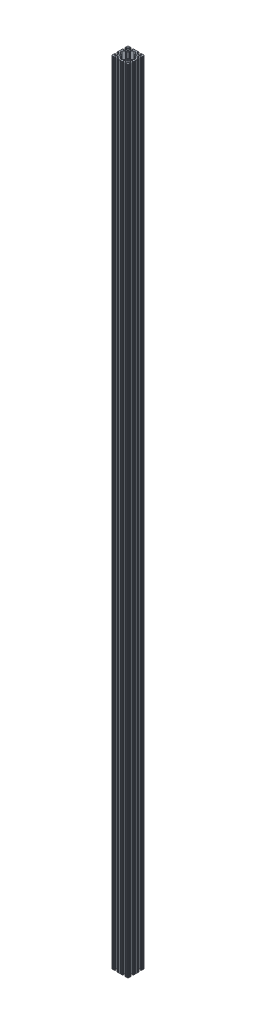
SolidWorks part; units mm, degrees
ref_plane "Piano frontale" through (0, 0, 0) normal (0, 0, 1) x (1, 0, 0)
ref_plane "Piano superiore" through (0, 0, 0) normal (0, 1, 0) x (1, 0, 0)
ref_plane "Piano destro" through (0, 0, 0) normal (1, 0, 0) x (0, 0, -1)
ref_plane "Piano1" through (0, 0, 0) normal (0, -1, 0) x (1, 0, 0)
sketch "Schizzo1" plane through (0, 0, 0) normal (0, -1, 0) x (1, 0, 0)
  line L0 (16.5037, -39.4963) -> (13.5247, -39.4963)
  line L1 (12.1105, -38.9105) -> (6.0284, -32.8284)
  line L2 (6.0284, -27.1716) -> (12.1105, -21.0895)
  line L3 (13.5247, -20.5037) -> (16.5037, -20.5037)
  line L4 (20.5037, -16.5037) -> (20.5037, -13.5247)
  line L5 (21.0895, -12.1105) -> (27.1716, -6.0284)
  line L6 (32.8284, -6.0284) -> (38.9105, -12.1105)
  line L7 (39.4963, -13.5247) -> (39.4963, -16.5037)
  line L8 (43.4963, -20.5037) -> (46.4753, -20.5037)
  line L9 (47.8895, -21.0895) -> (53.9716, -27.1716)
  line L10 (53.9716, -32.8284) -> (47.8895, -38.9105)
  line L11 (46.4753, -39.4963) -> (43.4963, -39.4963)
  line L12 (39.4963, -43.4963) -> (39.4963, -46.4753)
  line L13 (38.9105, -47.8895) -> (32.8284, -53.9716)
  line L14 (27.1716, -53.9716) -> (21.0895, -47.8895)
  line L15 (20.5037, -46.4753) -> (20.5037, -43.4963)
  line L16 (10.4, 0) -> (8.4, 0)
  line L17 (7.6, 0) -> (3, 0)
  line L18 (2.2, 0) -> (2, 0)
  line L19 (0, -2) -> (0, -2.2)
  line L20 (0, -3) -> (0, -7.6)
  line L21 (0, -8.4) -> (0, -10.4)
  line L22 (1.4, -11.8) -> (1.8, -11.8)
  line L23 (3.2, -10.4) -> (3.2, -7.3541)
  line L24 (4.5657, -6.7884) -> (8.9542, -11.177)
  line L25 (9.54, -12.5912) -> (9.54, -17.3716)
  line L26 (8.9542, -18.7858) -> (4.5657, -23.1743)
  line L27 (3.2, -22.6086) -> (3.2, -19.6)
  line L28 (1.8, -18.2) -> (1.4, -18.2)
  line L29 (0, -19.6) -> (0, -20.4)
  line L30 (0, -21.2) -> (0, -25.8)
  line L31 (0, -26.6) -> (0, -33.4)
  line L32 (0, -34.2) -> (0, -38.8)
  line L33 (0, -39.6) -> (0, -40.4)
  line L34 (1.4, -41.8) -> (1.8, -41.8)
  line L35 (3.2, -40.4) -> (3.2, -37.3914)
  line L36 (4.5657, -36.8257) -> (8.9542, -41.2142)
  line L37 (9.54, -42.6284) -> (9.54, -47.4088)
  line L38 (8.9542, -48.823) -> (4.5657, -53.2116)
  line L39 (3.2, -52.6459) -> (3.2, -49.6)
  line L40 (1.8, -48.2) -> (1.4, -48.2)
  line L41 (0, -49.6) -> (0, -51.6)
  line L42 (0, -52.4) -> (0, -57)
  line L43 (0, -57.8) -> (0, -58)
  line L44 (2, -60) -> (2.2, -60)
  line L45 (3, -60) -> (7.6, -60)
  line L46 (8.4, -60) -> (10.4, -60)
  line L47 (11.8, -58.6) -> (11.8, -58.2)
  line L48 (10.4, -56.8) -> (7.3541, -56.8)
  line L49 (6.7884, -55.4343) -> (11.177, -51.0458)
  line L50 (12.5912, -50.46) -> (17.3716, -50.46)
  line L51 (18.7858, -51.0458) -> (23.1743, -55.4343)
  line L52 (22.6086, -56.8) -> (19.6, -56.8)
  line L53 (18.2, -58.2) -> (18.2, -58.6)
  line L54 (19.6, -60) -> (20.4, -60)
  line L55 (21.2, -60) -> (25.8, -60)
  line L56 (26.6, -60) -> (33.4, -60)
  line L57 (34.2, -60) -> (38.8, -60)
  line L58 (39.6, -60) -> (40.4, -60)
  line L59 (41.8, -58.6) -> (41.8, -58.2)
  line L60 (40.4, -56.8) -> (37.3914, -56.8)
  line L61 (36.8257, -55.4343) -> (41.2142, -51.0458)
  line L62 (42.6284, -50.46) -> (47.4088, -50.46)
  line L63 (48.823, -51.0458) -> (53.2116, -55.4343)
  line L64 (52.6459, -56.8) -> (49.6, -56.8)
  line L65 (48.2, -58.2) -> (48.2, -58.6)
  line L66 (49.6, -60) -> (51.6, -60)
  line L67 (52.4, -60) -> (57, -60)
  line L68 (57.8, -60) -> (58, -60)
  line L69 (60, -58) -> (60, -57.8)
  line L70 (60, -57) -> (60, -52.4)
  line L71 (60, -51.6) -> (60, -49.6)
  line L72 (58.6, -48.2) -> (58.2, -48.2)
  line L73 (56.8, -49.6) -> (56.8, -52.6459)
  line L74 (55.4343, -53.2116) -> (51.0458, -48.823)
  line L75 (50.46, -47.4088) -> (50.46, -42.6284)
  line L76 (51.0458, -41.2142) -> (55.4343, -36.8257)
  line L77 (56.8, -37.3914) -> (56.8, -40.4)
  line L78 (58.2, -41.8) -> (58.6, -41.8)
  line L79 (60, -40.4) -> (60, -39.6)
  line L80 (60, -38.8) -> (60, -34.2)
  line L81 (60, -33.4) -> (60, -26.6)
  line L82 (60, -25.8) -> (60, -21.2)
  line L83 (60, -20.4) -> (60, -19.6)
  line L84 (58.6, -18.2) -> (58.2, -18.2)
  line L85 (56.8, -19.6) -> (56.8, -22.6086)
  line L86 (55.4343, -23.1743) -> (51.0458, -18.7858)
  line L87 (50.46, -17.3716) -> (50.46, -12.5912)
  line L88 (51.0458, -11.177) -> (55.4343, -6.7884)
  line L89 (56.8, -7.3541) -> (56.8, -10.4)
  line L90 (58.2, -11.8) -> (58.6, -11.8)
  line L91 (60, -10.4) -> (60, -8.4)
  line L92 (60, -7.6) -> (60, -3)
  line L93 (60, -2.2) -> (60, -2)
  line L94 (58, 0) -> (57.8, 0)
  line L95 (57, 0) -> (52.4, 0)
  line L96 (51.6, 0) -> (49.6, 0)
  line L97 (48.2, -1.4) -> (48.2, -1.8)
  line L98 (49.6, -3.2) -> (52.6459, -3.2)
  line L99 (53.2116, -4.5657) -> (48.823, -8.9542)
  line L100 (47.4088, -9.54) -> (42.6284, -9.54)
  line L101 (41.2142, -8.9542) -> (36.8257, -4.5657)
  line L102 (37.3914, -3.2) -> (40.4, -3.2)
  line L103 (41.8, -1.8) -> (41.8, -1.4)
  line L104 (40.4, 0) -> (39.6, 0)
  line L105 (38.8, 0) -> (34.2, 0)
  line L106 (33.4, 0) -> (26.6, 0)
  line L107 (25.8, 0) -> (21.2, 0)
  line L108 (20.4, 0) -> (19.6, 0)
  line L109 (18.2, -1.4) -> (18.2, -1.8)
  line L110 (19.6, -3.2) -> (22.6086, -3.2)
  line L111 (23.1743, -4.5657) -> (18.7858, -8.9542)
  line L112 (17.3716, -9.54) -> (12.5912, -9.54)
  line L113 (11.177, -8.9542) -> (6.7884, -4.5657)
  line L114 (7.3541, -3.2) -> (10.4, -3.2)
  line L115 (11.8, -1.8) -> (11.8, -1.4)
  arc A0 (13.5247, -39.4963) -> (12.1105, -38.9105) centre (13.5247, -37.4963) cw
  arc A1 (6.0284, -32.8284) -> (6.0284, -27.1716) centre (8.8569, -30) cw
  arc A2 (12.1105, -21.0895) -> (13.5247, -20.5037) centre (13.5247, -22.5037) cw
  arc A3 (16.5037, -20.5037) -> (20.5037, -16.5037) centre (16.5037, -16.5037) ccw
  arc A4 (20.5037, -13.5247) -> (21.0895, -12.1105) centre (22.5037, -13.5247) cw
  arc A5 (27.1716, -6.0284) -> (32.8284, -6.0284) centre (30, -8.8569) cw
  arc A6 (38.9105, -12.1105) -> (39.4963, -13.5247) centre (37.4963, -13.5247) cw
  arc A7 (39.4963, -16.5037) -> (43.4963, -20.5037) centre (43.4963, -16.5037) ccw
  arc A8 (46.4753, -20.5037) -> (47.8895, -21.0895) centre (46.4753, -22.5037) cw
  arc A9 (53.9716, -27.1716) -> (53.9716, -32.8284) centre (51.1431, -30) cw
  arc A10 (47.8895, -38.9105) -> (46.4753, -39.4963) centre (46.4753, -37.4963) cw
  arc A11 (43.4963, -39.4963) -> (39.4963, -43.4963) centre (43.4963, -43.4963) ccw
  arc A12 (39.4963, -46.4753) -> (38.9105, -47.8895) centre (37.4963, -46.4753) cw
  arc A13 (32.8284, -53.9716) -> (27.1716, -53.9716) centre (30, -51.1431) cw
  arc A14 (21.0895, -47.8895) -> (20.5037, -46.4753) centre (22.5037, -46.4753) cw
  arc A15 (20.5037, -43.4963) -> (16.5037, -39.4963) centre (16.5037, -43.4963) ccw
  circle A16 centre (15.0037, -15.0037) radius 2.62
  circle A17 centre (44.9963, -15.0037) radius 2.62
  circle A18 centre (44.9963, -44.9963) radius 2.62
  circle A19 centre (15.0037, -44.9963) radius 2.62
  arc A20 (11.8, -1.4) -> (10.4, 0) centre (10.4, -1.4) ccw
  arc A21 (8.4, 0) -> (7.6, 0) centre (8, 0) cw
  arc A22 (3, 0) -> (2.2, 0) centre (2.6, 0) cw
  arc A23 (2, 0) -> (0, -2) centre (2, -2) ccw
  arc A24 (0, -2.2) -> (0, -3) centre (0, -2.6) cw
  arc A25 (0, -7.6) -> (0, -8.4) centre (0, -8) cw
  arc A26 (0, -10.4) -> (1.4, -11.8) centre (1.4, -10.4) ccw
  arc A27 (1.8, -11.8) -> (3.2, -10.4) centre (1.8, -10.4) ccw
  arc A28 (3.2, -7.3541) -> (4.5657, -6.7884) centre (4, -7.3541) cw
  arc A29 (8.9542, -11.177) -> (9.54, -12.5912) centre (7.54, -12.5912) cw
  arc A30 (9.54, -17.3716) -> (8.9542, -18.7858) centre (7.54, -17.3716) cw
  arc A31 (4.5657, -23.1743) -> (3.2, -22.6086) centre (4, -22.6086) cw
  arc A32 (3.2, -19.6) -> (1.8, -18.2) centre (1.8, -19.6) ccw
  arc A33 (1.4, -18.2) -> (0, -19.6) centre (1.4, -19.6) ccw
  arc A34 (0, -20.4) -> (0, -21.2) centre (0, -20.8) cw
  arc A35 (0, -25.8) -> (0, -26.6) centre (0, -26.2) cw
  arc A36 (0, -33.4) -> (0, -34.2) centre (0, -33.8) cw
  arc A37 (0, -38.8) -> (0, -39.6) centre (0, -39.2) cw
  arc A38 (0, -40.4) -> (1.4, -41.8) centre (1.4, -40.4) ccw
  arc A39 (1.8, -41.8) -> (3.2, -40.4) centre (1.8, -40.4) ccw
  arc A40 (3.2, -37.3914) -> (4.5657, -36.8257) centre (4, -37.3914) cw
  arc A41 (8.9542, -41.2142) -> (9.54, -42.6284) centre (7.54, -42.6284) cw
  arc A42 (9.54, -47.4088) -> (8.9542, -48.823) centre (7.54, -47.4088) cw
  arc A43 (4.5657, -53.2116) -> (3.2, -52.6459) centre (4, -52.6459) cw
  arc A44 (3.2, -49.6) -> (1.8, -48.2) centre (1.8, -49.6) ccw
  arc A45 (1.4, -48.2) -> (0, -49.6) centre (1.4, -49.6) ccw
  arc A46 (0, -51.6) -> (0, -52.4) centre (0, -52) cw
  arc A47 (0, -57) -> (0, -57.8) centre (0, -57.4) cw
  arc A48 (0, -58) -> (2, -60) centre (2, -58) ccw
  arc A49 (2.2, -60) -> (3, -60) centre (2.6, -60) cw
  arc A50 (7.6, -60) -> (8.4, -60) centre (8, -60) cw
  arc A51 (10.4, -60) -> (11.8, -58.6) centre (10.4, -58.6) ccw
  arc A52 (11.8, -58.2) -> (10.4, -56.8) centre (10.4, -58.2) ccw
  arc A53 (7.3541, -56.8) -> (6.7884, -55.4343) centre (7.3541, -56) cw
  arc A54 (11.177, -51.0458) -> (12.5912, -50.46) centre (12.5912, -52.46) cw
  arc A55 (17.3716, -50.46) -> (18.7858, -51.0458) centre (17.3716, -52.46) cw
  arc A56 (23.1743, -55.4343) -> (22.6086, -56.8) centre (22.6086, -56) cw
  arc A57 (19.6, -56.8) -> (18.2, -58.2) centre (19.6, -58.2) ccw
  arc A58 (18.2, -58.6) -> (19.6, -60) centre (19.6, -58.6) ccw
  arc A59 (20.4, -60) -> (21.2, -60) centre (20.8, -60) cw
  arc A60 (25.8, -60) -> (26.6, -60) centre (26.2, -60) cw
  arc A61 (33.4, -60) -> (34.2, -60) centre (33.8, -60) cw
  arc A62 (38.8, -60) -> (39.6, -60) centre (39.2, -60) cw
  arc A63 (40.4, -60) -> (41.8, -58.6) centre (40.4, -58.6) ccw
  arc A64 (41.8, -58.2) -> (40.4, -56.8) centre (40.4, -58.2) ccw
  arc A65 (37.3914, -56.8) -> (36.8257, -55.4343) centre (37.3914, -56) cw
  arc A66 (41.2142, -51.0458) -> (42.6284, -50.46) centre (42.6284, -52.46) cw
  arc A67 (47.4088, -50.46) -> (48.823, -51.0458) centre (47.4088, -52.46) cw
  arc A68 (53.2116, -55.4343) -> (52.6459, -56.8) centre (52.6459, -56) cw
  arc A69 (49.6, -56.8) -> (48.2, -58.2) centre (49.6, -58.2) ccw
  arc A70 (48.2, -58.6) -> (49.6, -60) centre (49.6, -58.6) ccw
  arc A71 (51.6, -60) -> (52.4, -60) centre (52, -60) cw
  arc A72 (57, -60) -> (57.8, -60) centre (57.4, -60) cw
  arc A73 (58, -60) -> (60, -58) centre (58, -58) ccw
  arc A74 (60, -57.8) -> (60, -57) centre (60, -57.4) cw
  arc A75 (60, -52.4) -> (60, -51.6) centre (60, -52) cw
  arc A76 (60, -49.6) -> (58.6, -48.2) centre (58.6, -49.6) ccw
  arc A77 (58.2, -48.2) -> (56.8, -49.6) centre (58.2, -49.6) ccw
  arc A78 (56.8, -52.6459) -> (55.4343, -53.2116) centre (56, -52.6459) cw
  arc A79 (51.0458, -48.823) -> (50.46, -47.4088) centre (52.46, -47.4088) cw
  arc A80 (50.46, -42.6284) -> (51.0458, -41.2142) centre (52.46, -42.6284) cw
  arc A81 (55.4343, -36.8257) -> (56.8, -37.3914) centre (56, -37.3914) cw
  arc A82 (56.8, -40.4) -> (58.2, -41.8) centre (58.2, -40.4) ccw
  arc A83 (58.6, -41.8) -> (60, -40.4) centre (58.6, -40.4) ccw
  arc A84 (60, -39.6) -> (60, -38.8) centre (60, -39.2) cw
  arc A85 (60, -34.2) -> (60, -33.4) centre (60, -33.8) cw
  arc A86 (60, -26.6) -> (60, -25.8) centre (60, -26.2) cw
  arc A87 (60, -21.2) -> (60, -20.4) centre (60, -20.8) cw
  arc A88 (60, -19.6) -> (58.6, -18.2) centre (58.6, -19.6) ccw
  arc A89 (58.2, -18.2) -> (56.8, -19.6) centre (58.2, -19.6) ccw
  arc A90 (56.8, -22.6086) -> (55.4343, -23.1743) centre (56, -22.6086) cw
  arc A91 (51.0458, -18.7858) -> (50.46, -17.3716) centre (52.46, -17.3716) cw
  arc A92 (50.46, -12.5912) -> (51.0458, -11.177) centre (52.46, -12.5912) cw
  arc A93 (55.4343, -6.7884) -> (56.8, -7.3541) centre (56, -7.3541) cw
  arc A94 (56.8, -10.4) -> (58.2, -11.8) centre (58.2, -10.4) ccw
  arc A95 (58.6, -11.8) -> (60, -10.4) centre (58.6, -10.4) ccw
  arc A96 (60, -8.4) -> (60, -7.6) centre (60, -8) cw
  arc A97 (60, -3) -> (60, -2.2) centre (60, -2.6) cw
  arc A98 (60, -2) -> (58, 0) centre (58, -2) ccw
  arc A99 (57.8, 0) -> (57, 0) centre (57.4, 0) cw
  arc A100 (52.4, 0) -> (51.6, 0) centre (52, 0) cw
  arc A101 (49.6, 0) -> (48.2, -1.4) centre (49.6, -1.4) ccw
  arc A102 (48.2, -1.8) -> (49.6, -3.2) centre (49.6, -1.8) ccw
  arc A103 (52.6459, -3.2) -> (53.2116, -4.5657) centre (52.6459, -4) cw
  arc A104 (48.823, -8.9542) -> (47.4088, -9.54) centre (47.4088, -7.54) cw
  arc A105 (42.6284, -9.54) -> (41.2142, -8.9542) centre (42.6284, -7.54) cw
  arc A106 (36.8257, -4.5657) -> (37.3914, -3.2) centre (37.3914, -4) cw
  arc A107 (40.4, -3.2) -> (41.8, -1.8) centre (40.4, -1.8) ccw
  arc A108 (41.8, -1.4) -> (40.4, 0) centre (40.4, -1.4) ccw
  arc A109 (39.6, 0) -> (38.8, 0) centre (39.2, 0) cw
  arc A110 (34.2, 0) -> (33.4, 0) centre (33.8, 0) cw
  arc A111 (26.6, 0) -> (25.8, 0) centre (26.2, 0) cw
  arc A112 (21.2, 0) -> (20.4, 0) centre (20.8, 0) cw
  arc A113 (19.6, 0) -> (18.2, -1.4) centre (19.6, -1.4) ccw
  arc A114 (18.2, -1.8) -> (19.6, -3.2) centre (19.6, -1.8) ccw
  arc A115 (22.6086, -3.2) -> (23.1743, -4.5657) centre (22.6086, -4) cw
  arc A116 (18.7858, -8.9542) -> (17.3716, -9.54) centre (17.3716, -7.54) cw
  arc A117 (12.5912, -9.54) -> (11.177, -8.9542) centre (12.5912, -7.54) cw
  arc A118 (6.7884, -4.5657) -> (7.3541, -3.2) centre (7.3541, -4) cw
  arc A119 (10.4, -3.2) -> (11.8, -1.8) centre (10.4, -1.8) ccw
  dimension "D1" = 60
  dimension "D2" = 60
extrude "Estrusione-Estrusione1" add sketch "Schizzo1" against normal blind 2900
